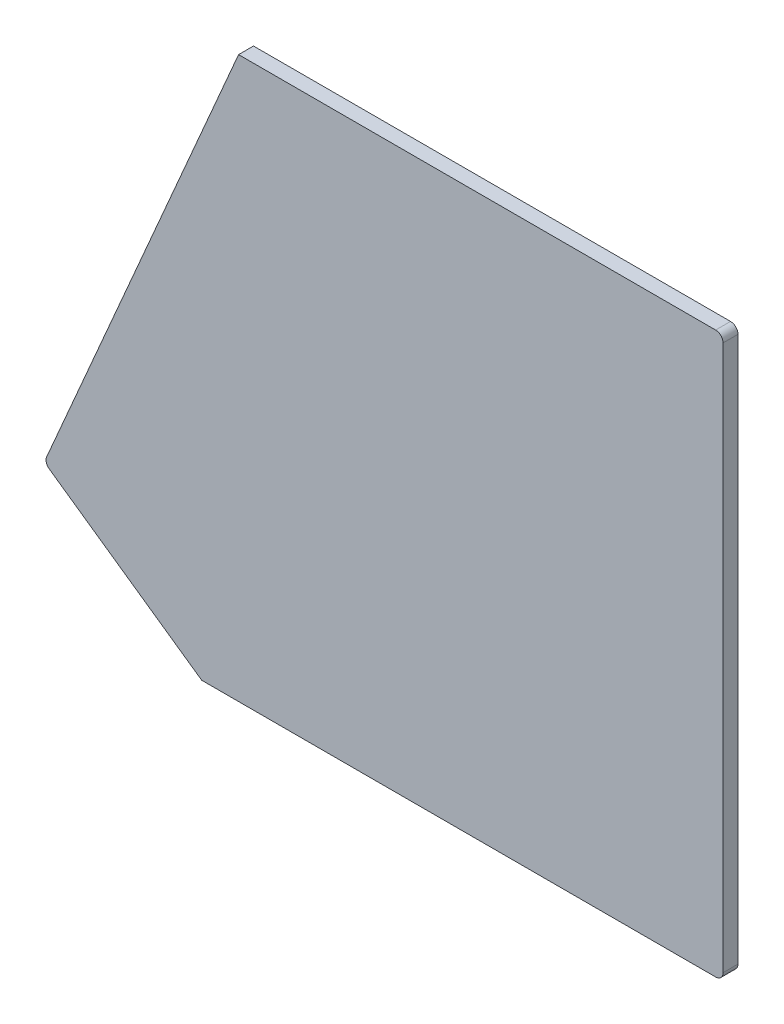
SolidWorks part; units mm, degrees
ref_plane "Plano frontal" through (0, 0, 0) normal (0, 0, 1) x (1, 0, 0)
ref_plane "Plano superior" through (0, 0, 0) normal (0, 1, 0) x (1, 0, 0)
ref_plane "Plano direito" through (0, 0, 0) normal (1, 0, 0) x (0, 0, -1)
sketch "Esboço1" plane through (0, 0, 0) normal (0, 0, 1) x (1, 0, 0)
  line L0 (0, 0) -> (138, 0)
  line L1 (140, 2) -> (140, 148.4543)
  line L2 (138, 150.4543) -> (9.8994, 150.4543)
  line L3 (9.8994, 150.4543) -> (-41.6465, 31.1101)
  line L4 (-40.9576, 28.6788) -> (0, 0)
  line L5 (0, 0) -> (-36.2791, 0) construction
  arc A0 (-41.6465, 31.1101) -> (-40.9576, 28.6788) centre (-39.8104, 30.3171) ccw
  arc A1 (138, 0) -> (140, 2) centre (138, 2) ccw
  arc A2 (140, 148.4543) -> (138, 150.4543) centre (138, 148.4543) ccw
  point P11 (140, 0)
  dimension "D1" = 2
  dimension "D7" = 2
  dimension "D2" = 35
  dimension "D3" = 50
  dimension "D4" = 101.64
  dimension "D5" = 130
  dimension "D6" = 140
extrude "Ressalto-extrusão1" add sketch "Esboço1" along normal blind 4
